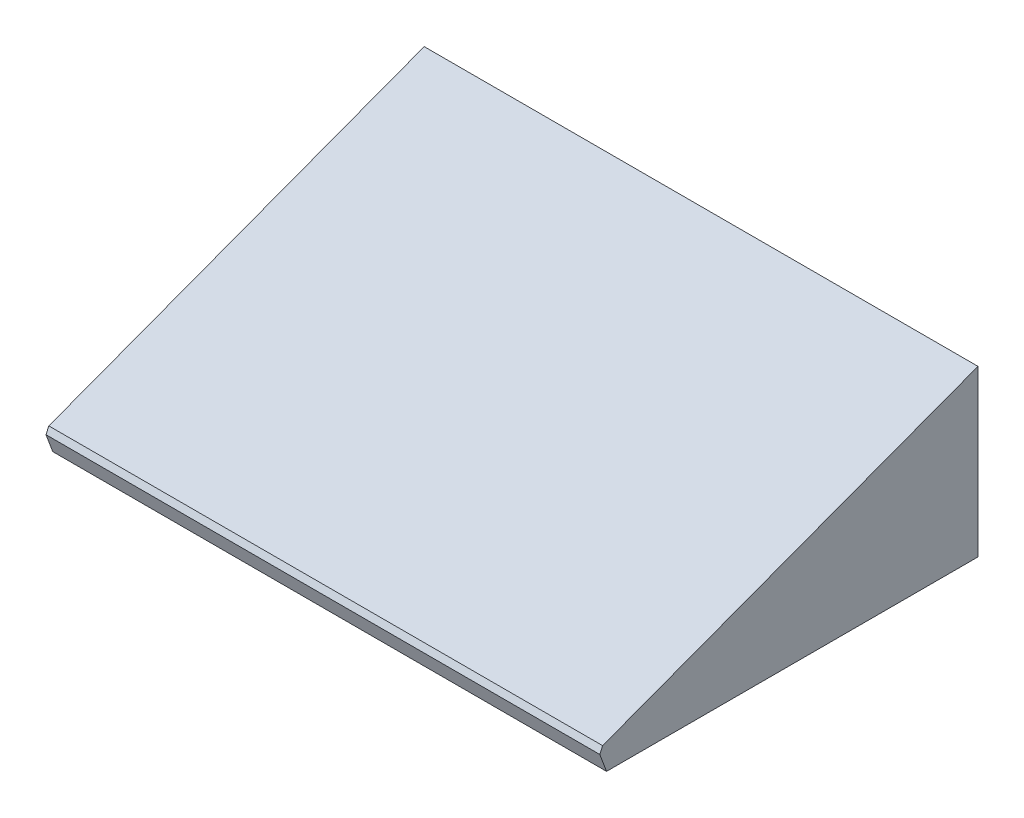
SolidWorks part; units mm, degrees
ref_plane "Front Plane" through (0, 0, 0) normal (0, 0, 1) x (1, 0, 0)
ref_plane "Top Plane" through (0, 0, 0) normal (0, 1, 0) x (1, 0, 0)
ref_plane "Right Plane" through (0, 0, 0) normal (1, 0, 0) x (0, 0, -1)
sketch "Sketch1" plane through (0, 0, 0) normal (1, 0, 0) x (0, 0, -1)
  line L0 (-40, 0) -> (40, 0)
  line L1 (40, 0) -> (40, 30)
  line L2 (40, 30) -> (-40, 0)
  point P3 (0, 0)
  dimension "D1" = 80
  dimension "D2" = 30
extrude "Boss-Extrude1" add sketch "Sketch1" along normal blind 120
sketch "Sketch2" plane through (0, 0, 1.8208) normal (0, 1, 0) x (1, 0, 0)
  line L0 (0, 41.8208) -> (0, -38.1792) construction
  line L1 (4.75, 38.8208) -> (89.75, 38.8208)
  line L2 (4.75, 38.8208) -> (4.75, 16.8208)
  line L3 (4.75, 16.8208) -> (89.75, 16.8208)
  line L4 (89.75, 38.8208) -> (89.75, 16.8208)
  line L5 (120, 41.8208) -> (0, 41.8208) construction
  dimension "D1" = 85
  dimension "D2" = 22
  dimension "D3" = 4.75
  dimension "D4" = 3
extrude "Cut-Extrude1" cut sketch "Sketch2" along normal blind 15.5
sketch "Sketch3" plane through (0, 0, 0) normal (0, -1, 0) x (1, 0, 0)
  line L0 (89.75, -37) -> (4.75, -37) construction
  line L1 (113.55, -37) -> (82.05, -37)
  line L2 (113.55, -37) -> (113.55, 34)
  line L3 (113.55, 34) -> (82.05, 34)
  line L4 (82.05, -37) -> (82.05, 34)
  line L5 (89.75, -15) -> (89.75, -37) construction
  dimension "D1" = 31.5
  dimension "D2" = 71
  dimension "D3" = 7.7
extrude "Cut-Extrude2" cut sketch "Sketch3" against normal blind 2
sketch "Sketch4" plane through (0, 0, 0) normal (0, -1, 0) x (1, 0, 0)
  line L0 (113.55, -37) -> (4.75, -37) construction
  line L1 (108.55, -24) -> (82.05, -24)
  line L2 (108.55, -24) -> (108.55, 18)
  line L3 (108.55, 18) -> (82.05, 18)
  line L4 (82.05, -24) -> (82.05, 18)
  line L5 (113.55, -37) -> (113.55, 34) construction
  line L6 (82.05, 34) -> (82.05, -15) construction
  dimension "D1" = 13
  dimension "D2" = 5
  dimension "D3" = 42
extrude "Cut-Extrude3" cut sketch "Sketch4" against normal offset from surface (6 mm away) 4 up to face at (95.1167, 2, -6)
sketch "Sketch5" plane through (0, 0, 0) normal (0, -1, 0) x (1, 0, 0)
  line L0 (4.75, -37) -> (4.75, -15) construction
  line L1 (82.05, -15) -> (4.75, -15)
  line L2 (82.05, -15) -> (82.05, 15)
  line L3 (82.05, 15) -> (4.75, 15)
  line L4 (4.75, -15) -> (4.75, 15)
  line L5 (113.55, 34) -> (82.05, 34) construction
  dimension "D1" = 19
extrude "Cut-Extrude4" cut sketch "Sketch5" against normal blind 2
sketch "Sketch6" plane through (0, 0, 0) normal (0, -1, 0) x (1, 0, 0)
  line L0 (4.75, -15) -> (82.05, -15) construction
  line L1 (82.05, 18) -> (4.75, 18)
  line L2 (82.05, 18) -> (82.05, -15)
  line L3 (82.05, -15) -> (4.75, -15)
  line L4 (4.75, 18) -> (4.75, -15)
  line L5 (4.75, 15) -> (4.75, -15) construction
  point P6 (4.8579, -16.9627)
extrude "Cut-Extrude5" cut sketch "Sketch6" against normal offset from surface (5 mm away) 3 up to face at (98.475, 2, -2.25)
sketch "Sketch7" plane through (0, 5, 0) normal (0, -1, 0) x (1, 0, 0)
  line L0 (89.75, -15) -> (82.05, -15) construction
  line L1 (4.75, 18) -> (12.75, 18)
  line L2 (4.75, 18) -> (4.75, -15)
  line L3 (4.75, -15) -> (12.75, -15)
  line L4 (12.75, 18) -> (12.75, -15)
  point P7 (4.8634, 17.0205)
  point P8 (0, 0)
  point P9 (4.75, 18)
  dimension "D1" = 8
extrude "Cut-Extrude6" cut sketch "Sketch7" against normal blind 5
sketch "Sketch8" plane through (0, 13.1507, 4.9315) normal (0, 0.9363, 0.3511) x (1, 0, 0)
  line L4 (0, 47.9869) -> (0, -37.4532)
  line L5 (0, -37.4532) -> (120, -37.4532)
  line L6 (120, -37.4532) -> (120, 47.9869)
  line L7 (120, 47.9869) -> (0, 47.9869)
  line L8 (0, 47.9869) -> (0, -37.4532)
  line L9 (0, -37.4532) -> (120, -37.4532)
  line L10 (120, -37.4532) -> (120, 47.9869)
  line L11 (120, 47.9869) -> (0, 47.9869)
  dimension "D1" = 0
extrude "Boss-Extrude2" add sketch "Sketch8" along normal blind 5
chamfer "Chamfer1" distance 1 angle 45 4 edges at (120, 19.6816, 1.7556) (60, 4.6816, 41.7556) (0, 19.6816, 1.7556) (60, 34.6816, -38.2444)
sketch "Sketch9" plane through (0, 0, 0) normal (0, -1, 0) x (1, 0, 0)
  line L0 (120, -40) -> (0, -40) construction
  line L1 (120, 41.4045) -> (116.55, 41.4045)
  line L2 (120, 41.4045) -> (120, -40)
  line L3 (120, -40) -> (116.55, -40)
  line L4 (116.55, 41.4045) -> (116.55, -40)
  line L5 (113.55, -37) -> (113.55, 34) construction
  dimension "D1" = 3
extrude "Cut-Extrude7" cut sketch "Sketch9" against normal through all both and the other way through all
sketch "Sketch10" plane through (0, 0, 0) normal (0, -1, 0) x (1, 0, 0)
  line L0 (116.55, 40) -> (0, 40) construction
  line L1 (82.05, 34) -> (82.05, 18) construction
  line L2 (116.55, -40) -> (0, -40) construction
  line L4 (81.05, 31) -> (71.05, 31) construction
  line L5 (62.75, 31) -> (52.75, 31) construction
  line L7 (49.95, 31) -> (39.95, 31) construction
  line L8 (37.15, 31) -> (27.15, 31) construction
  line L9 (24.35, 31) -> (14.35, 31) construction
  text T0 "R" font "Impact" height in points 32
  text T1 "M" font "Impact" height in points 32
  text T2 "J" font "Impact" height in points 32
  text T3 "P" font "Impact" height in points 32
  text T4 "C" font "Impact" height in points 32
  point P2 (0, 0)
  point P15 (78.3572, 29.834)
  point P17 (76.05, 31)
  point P18 (57.75, 31)
  point P19 (44.95, 31)
  point P20 (32.15, 31)
  point P21 (19.35, 31)
  dimension "D1" = 10
  dimension "D3" = 18.3
  dimension "D4" = 12.8
  dimension "D5" = 12.8
  dimension "D6" = 12.8
  dimension "D7" = 40
  dimension "D2" = 9
  dimension "D8" = 1
extrude "Cut-Extrude8" cut sketch "Sketch10" against normal blind 2
sketch "Sketch11" plane through (0, 0, 0) normal (0, -1, 0) x (1, 0, 0)
  line L0 (89.75, -37) -> (113.55, -37) construction
  line L1 (0, -40) -> (116.55, -40)
  line L2 (0, -40) -> (0, -37)
  line L3 (0, -37) -> (116.55, -37)
  line L4 (116.55, -40) -> (116.55, -37)
  line L5 (116.55, -40) -> (116.55, 40) construction
  point P8 (114.8, -37)
extrude "Cut-Extrude9" cut sketch "Sketch11" against normal through all both and the other way through all
sketch "Sketch12" plane through (0, 6, 0) normal (0, -1, 0) x (1, 0, 0)
  line L0 (89.75, -37) -> (113.55, -37) construction
  line L1 (89.75, -24) -> (108.55, -24)
  line L2 (89.75, -24) -> (89.75, -37)
  line L3 (89.75, -37) -> (108.55, -37)
  line L4 (108.55, -24) -> (108.55, -37)
  line L5 (108.55, 18) -> (108.55, -24) construction
extrude "Cut-Extrude10" cut sketch "Sketch12" along normal up to next
sketch "Sketch14" plane through (0, 0, 0) normal (0, -1, 0) x (1, 0, 0)
  line L0 (4.75, -37) -> (4.75, 18) construction
  line L1 (82.05, 18) -> (4.75, 18)
  line L2 (82.05, 18) -> (82.05, 15)
  line L3 (82.05, 15) -> (4.75, 15)
  line L4 (4.75, 18) -> (4.75, 15)
  dimension "D1" = 3
extrude "Boss-Extrude3" add sketch "Sketch14" against normal up to next
sketch "Sketch15" plane through (0, 0, 0) normal (0, -1, 0) x (1, 0, 0)
  line L0 (0, 40) -> (0, -37) construction
  line L1 (0, -37) -> (1.75, -37)
  line L2 (0, -37) -> (0, 41.4045)
  line L3 (0, 41.4045) -> (1.75, 41.4045)
  line L4 (1.75, -37) -> (1.75, 41.4045)
  line L5 (0, -37) -> (4.75, -37) construction
  line L6 (116.55, 41.4045) -> (0, 41.4045) construction
  line L7 (4.75, -37) -> (4.75, 15) construction
  dimension "D1" = 3
extrude "Cut-Extrude11" cut sketch "Sketch15" against normal through all both and the other way through all
sketch "Sketch16" plane through (0, 0, 0) normal (0, -1, 0) x (1, 0, 0)
  line L0 (89.75, -37) -> (4.75, -37) construction
  line L1 (4.75, 15) -> (6.75, 15)
  line L2 (4.75, 15) -> (4.75, -37)
  line L3 (4.75, -37) -> (6.75, -37)
  line L4 (6.75, 15) -> (6.75, -37)
  dimension "D1" = 2
extrude "Boss-Extrude4" add sketch "Sketch16" against normal up to next
sketch "Sketch17" plane through (0, 5, 0) normal (0, -1, 0) x (1, 0, 0)
  line L1 (6.75, 15) -> (12.35, 15)
  line L2 (6.75, 15) -> (6.75, 3)
  line L3 (6.75, 3) -> (12.35, 3)
  line L4 (12.35, 15) -> (12.35, 3)
  dimension "D1" = 5.6
  dimension "D2" = 12
extrude "Boss-Extrude5" add sketch "Sketch17" along normal offset from surface (3 mm away) 2 contours L3 L4 L1 L2 up to face at (64.13, 0, 3)
sketch "Sketch18" plane through (0, 5, 0) normal (0, 1, 0) x (1, 0, 0)
  line L4 (6.75, -3) -> (6.75, -15)
  line L5 (6.75, -15) -> (12.35, -15)
  line L6 (12.35, -15) -> (12.35, -3)
  line L7 (12.35, -3) -> (6.75, -3)
  line L8 (6.75, -3) -> (6.75, -15)
  line L9 (6.75, -15) -> (12.35, -15)
  line L10 (12.35, -15) -> (12.35, -3)
  line L11 (12.35, -3) -> (6.75, -3)
  dimension "D1" = 0
extrude "Boss-Extrude6" add sketch "Sketch18" along normal up to next
sketch "Sketch19" plane through (0, 5, 0) normal (0, -1, 0) x (1, 0, 0)
  line L0 (12.75, -15) -> (12.75, 15) construction
  line L1 (12.35, 15) -> (12.75, 15)
  line L2 (12.35, 15) -> (12.35, 3)
  line L3 (12.35, 3) -> (12.75, 3)
  line L4 (12.75, 15) -> (12.75, 3)
  line L5 (12.35, 3) -> (6.75, 3) construction
  point P7 (12.55, 3)
extrude "Boss-Extrude7" add sketch "Sketch19" against normal up to next
sketch "Sketch20" plane through (0, 5, 0) normal (0, -1, 0) x (1, 0, 0)
  line L0 (82.05, 15) -> (82.05, -15) construction
  line L1 (12.35, 15) -> (82.05, 15)
  line L2 (12.35, 15) -> (12.35, 13.5)
  line L3 (12.35, 13.5) -> (82.05, 13.5)
  line L4 (82.05, 15) -> (82.05, 13.5)
  dimension "D1" = 1.5
extrude "Boss-Extrude8" add sketch "Sketch20" along normal offset from surface (3 mm away) 2 up to face at (64.13, 0, 3)
equation "\"D5@Sketch10\"=\"D4@Sketch10\""
equation "\"D6@Sketch10\"=\"D5@Sketch10\""
equation "\"D1@Sketch15\"=3"
equation "\"D1@Sketch16\"=2"
equation "\"D8@Sketch10\"=1"
